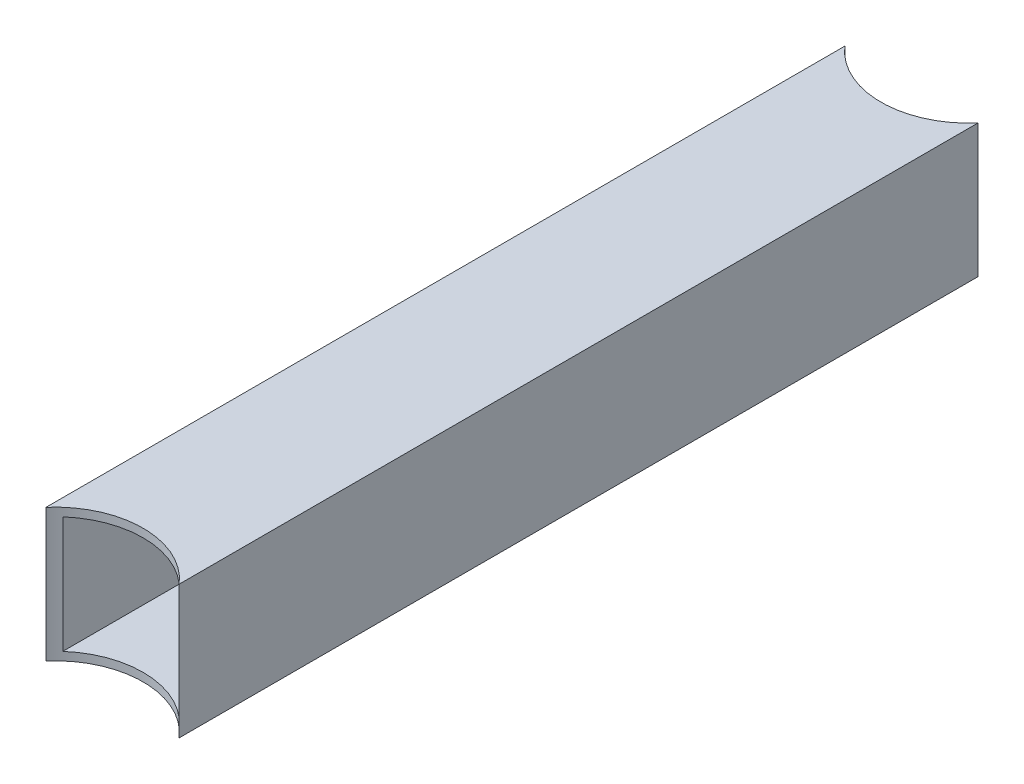
SolidWorks part; units mm, degrees
ref_plane "Front Plane" through (0, 0, 0) normal (0, 0, 1) x (1, 0, 0)
ref_plane "Top Plane" through (0, 0, 0) normal (0, 1, 0) x (1, 0, 0)
ref_plane "Right Plane" through (0, 0, 0) normal (1, 0, 0) x (0, 0, -1)
sketch "Sketch1" plane through (0, 0, 0) normal (0, 0, 1) x (1, 0, 0)
  line L1 (-12.7, 12.7) -> (12.7, 12.7)
  line L2 (-12.7, 12.7) -> (-12.7, -12.7)
  line L3 (-12.7, -12.7) -> (12.7, -12.7)
  line L4 (12.7, 12.7) -> (12.7, -12.7)
  line L5 (-12.7, 12.7) -> (12.7, -12.7) construction
  line L6 (-12.7, -12.7) -> (12.7, 12.7) construction
  line L7 (11.1125, -11.1125) -> (-11.1125, -11.1125)
  line L8 (11.1125, -11.1125) -> (11.1125, 11.1125)
  line L9 (11.1125, 11.1125) -> (-11.1125, 11.1125)
  line L10 (-11.1125, -11.1125) -> (-11.1125, 11.1125)
  line L11 (11.1125, -11.1125) -> (-11.1125, 11.1125) construction
  line L12 (11.1125, 11.1125) -> (-11.1125, -11.1125) construction
  point P0 (0, 0)
  point P6 (0, 0)
  dimension "D1" = 25.4
  dimension "D2" = 1.5875
extrude "Boss-Extrude1" add sketch "Sketch1" along normal blind 152.4
other "1in Square tube<1>"
sketch "Sketch2" plane through (0, 12.7, 0) normal (0, 1, 0) x (1, 0, 0)
  line L0 (12.7, 0) -> (-12.7, 0) construction
  line L1 (12.7, -152.4) -> (-12.7, -152.4) construction
  line L2 (-12.7, 0) -> (12.7, 0)
  line L3 (12.7, -152.4) -> (-12.7, -152.4)
  arc A0 (-12.7, 0) -> (12.7, 0) centre (0, 10.9427) ccw
  arc A1 (-12.7, -152.4) -> (12.7, -152.4) centre (0, -163.3427) cw
  dimension "D1" = 16.764
extrude "Cut-Extrude1" cut sketch "Sketch2" against normal through all
